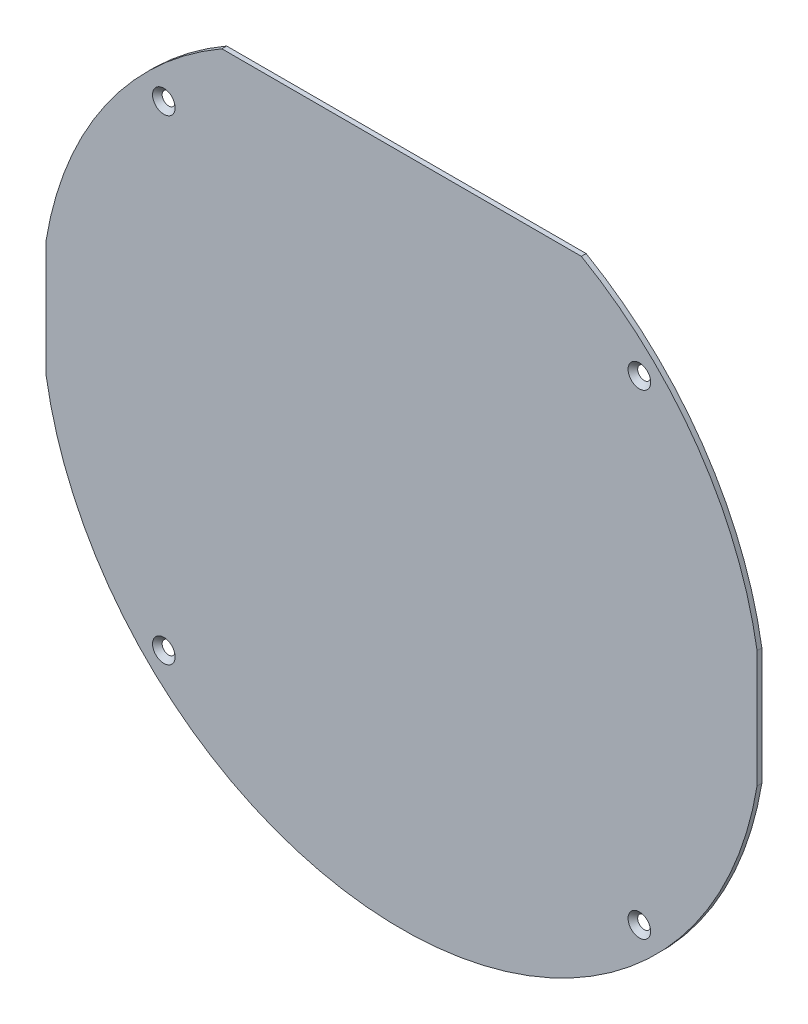
SolidWorks part; units mm, degrees
ref_plane "Face" through (0, 0, 0) normal (0, 0, 1) x (1, 0, 0)
ref_plane "Dessus" through (0, 0, 0) normal (0, 1, 0) x (1, 0, 0)
ref_plane "Droite" through (0, 0, 0) normal (1, 0, 0) x (0, 0, -1)
sketch "Esquisse1" plane through (0, 0, 0) normal (0, 0, 1) x (1, 0, 0)
  line L0 (-74.8331, 130) -> (74.8331, 130)
  line L1 (140, 0) -> (-140, 0) construction
  line L2 (-148, 24.4131) -> (-148, -24.4131)
  line L3 (98.9949, 98.9949) -> (-98.9949, -98.9949) construction
  line L4 (-98.9949, 98.9949) -> (98.9949, -98.9949) construction
  line L5 (148, 24.4131) -> (148, -24.4131)
  arc A0 (-74.8331, 130) -> (-148, 24.4131) centre (0, 0) ccw
  arc A1 (-148, -24.4131) -> (148, -24.4131) centre (0, 0) ccw
  circle A2 centre (0, 0) radius 140 construction
  circle A3 centre (-98.9949, 98.9949) radius 1.6
  circle A4 centre (-98.9949, -98.9949) radius 1.6
  circle A5 centre (98.9949, -98.9949) radius 1.6
  circle A6 centre (98.9949, 98.9949) radius 1.6
  arc A7 (148, 24.4131) -> (74.8331, 130) centre (0, 0) ccw
  dimension "D1" = 300
  dimension "D2" = 148
  dimension "D3" = 10
  dimension "D4" = 130
  dimension "D5" = 45
  dimension "D6" = 148
  dimension "D7" = 45
extrude "Boss.-Extru.1" add sketch "Esquisse1" along normal blind 2
hole_wizard "Fraisage pour vis à tête fraisée M42" positions "Esquisse5" profile "Esquisse4" countersink size "M4" standard "Din" end condition through all
sketch "Esquisse5" plane through (0, 0, 2) normal (0, 0, 1) x (1, 0, 0)
  point P0 (98.9949, 98.9949)
  point P4 (-98.9949, 98.9949)
  point P8 (98.9949, -98.9949)
  point P11 (-98.9949, -98.9949)
sketch "Esquisse4" plane through (98.9949, 98.9949, 2) normal (1, 0, 0) x (0, -1, 0)
  line L0 (0, 0) -> (0, 2)
  line L1 (0, 2) -> (2.25, 2)
  line L2 (2.25, 2) -> (2.25, 2.45)
  line L3 (2.25, 2.45) -> (4.7, 0)
  line L5 (4.7, 0) -> (0, 0)
  line L6 (-2.25, 2.45) -> (-4.7, 0) construction
  line L11 (0, -6.35) -> (0, 107.95) construction
  dimension "Diamètre du perçage jusqu'au prochain" = 4.5
  dimension "Profondeur du perçage jusqu'au prochain" = 2
  dimension "Diamètre du fraisage entrant" = 9.4
  dimension "Angle du fraisage entrant" = 90
